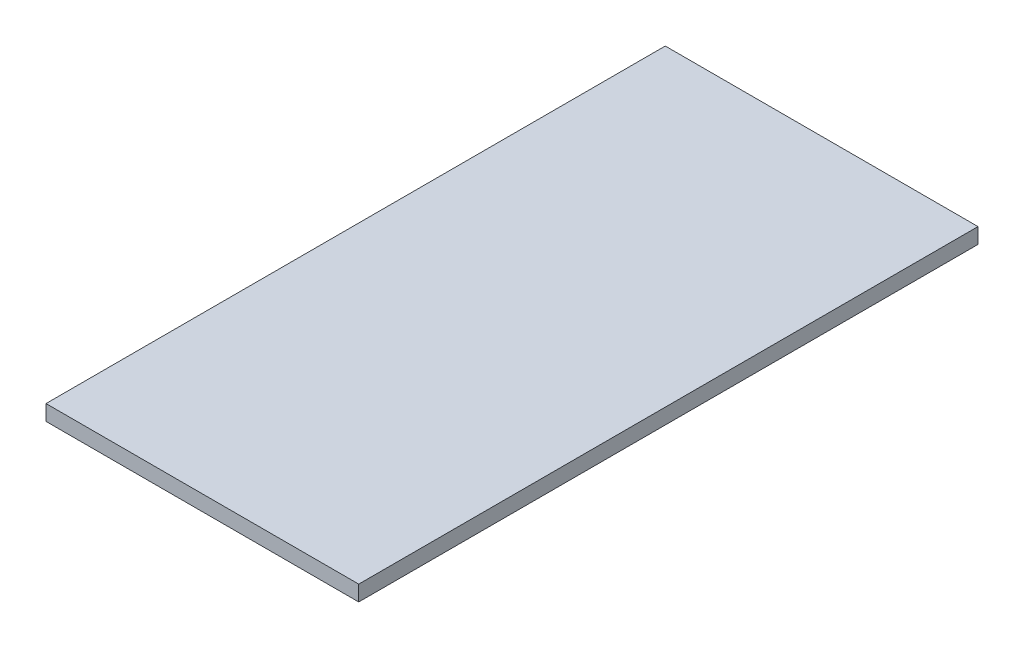
SolidWorks part; units mm, degrees
material "아크릴(내충격성)"
ref_plane "정면" through (0, 0, 0) normal (0, 0, 1) x (1, 0, 0)
ref_plane "윗면" through (0, 0, 0) normal (0, 1, 0) x (1, 0, 0)
ref_plane "우측면" through (0, 0, 0) normal (1, 0, 0) x (0, 0, -1)
sketch "스케치1" plane through (0, 0, 0) normal (0, 1, 0) x (1, 0, 0)
  line L1 (-50.5, 100) -> (50.5, 100)
  line L2 (-50.5, 100) -> (-50.5, -100)
  line L3 (-50.5, -100) -> (50.5, -100)
  line L4 (50.5, 100) -> (50.5, -100)
  line L5 (-50.5, 100) -> (50.5, -100) construction
  line L6 (-50.5, -100) -> (50.5, 100) construction
  point P0 (0, 0)
  dimension "D1" = 101
  dimension "D2" = 200
extrude "보스-돌출1" add sketch "스케치1" along normal blind 5
